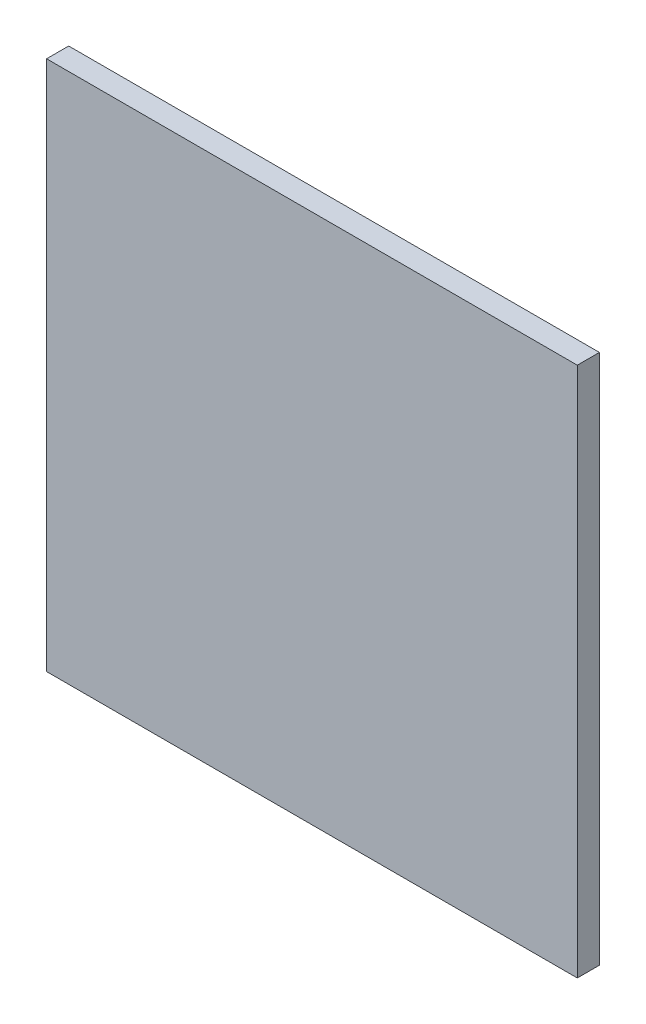
SolidWorks part; units mm, degrees
ref_plane "Alzado" through (0, 0, 0) normal (0, 0, 1) x (1, 0, 0)
ref_plane "Planta" through (0, 0, 0) normal (0, 1, 0) x (1, 0, 0)
ref_plane "Vista lateral" through (0, 0, 0) normal (1, 0, 0) x (0, 0, -1)
sketch "Croquis1" plane through (0, 0, 0) normal (0, 0, 1) x (1, 0, 0)
  line L1 (-60, 60) -> (60, 60)
  line L2 (-60, 60) -> (-60, -60)
  line L3 (-60, -60) -> (60, -60)
  line L4 (60, 60) -> (60, -60)
  line L5 (-60, 60) -> (60, -60) construction
  line L6 (-60, -60) -> (60, 60) construction
  point P0 (0, 0)
extrude "Saliente-Extruir1" add sketch "Croquis1" along normal blind 5
sketch "Croquis3" plane through (0, 0, 0) normal (0, 0, -1) x (-1, 0, 0)
  line L1 (-50, 50) -> (50, 50)
  line L2 (-50, 50) -> (-50, -50)
  line L3 (-50, -50) -> (50, -50)
  line L4 (50, 50) -> (50, -50)
  line L5 (-50, 50) -> (50, -50) construction
  line L6 (-50, -50) -> (50, 50) construction
  point P0 (0, 0)
  dimension "D1" = 100
  dimension "D2" = 100
extrude "Cortar-Extruir1" cut sketch "Croquis3" against normal blind 1
